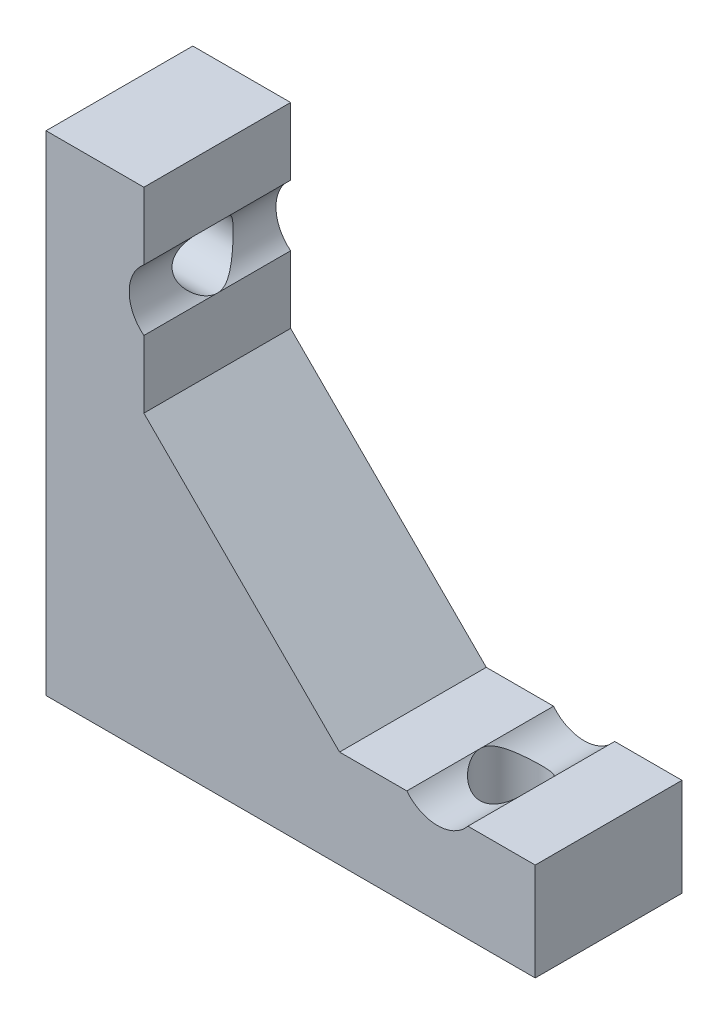
SolidWorks part; units mm, degrees
material "Aleación 1060"
ref_plane "Alzado" through (0, 0, 0) normal (0, 0, 1) x (1, 0, 0)
ref_plane "Planta" through (0, 0, 0) normal (0, 1, 0) x (1, 0, 0)
ref_plane "Vista lateral" through (0, 0, 0) normal (1, 0, 0) x (0, 0, -1)
sketch "Croquis1" plane through (0, 0, 0) normal (0, 0, 1) x (1, 0, 0)
  line L0 (0, 0) -> (0, 20)
  line L1 (0, 0) -> (20, 0)
  line L2 (0, 20) -> (4, 20)
  line L3 (20, 0) -> (20, 4)
  line L4 (4, 20) -> (4, 12)
  line L5 (20, 4) -> (12, 4)
  line L6 (4, 12) -> (12, 4)
  dimension "D1" = 20
  dimension "D2" = 20
  dimension "D3" = 4
  dimension "D4" = 4
  dimension "D5" = 8
  dimension "D6" = 8
extrude "Saliente-Extruir1" add sketch "Croquis1" along normal blind 6
sketch "Croquis3" plane through (0, 4, 0) normal (0, 1, 0) x (1, 0, 0)
  line L0 (20, -6) -> (20, 0) construction
  line L1 (20, 0) -> (12, 0) construction
  circle A0 centre (16, -3) radius 1.25
  point P5 (16, 0)
  point P9 (20, -3)
  dimension "D1" = 2.5
extrude "Cortar-Extruir1" cut sketch "Croquis3" against normal up to vertex (4 mm away)
sketch "Croquis4" plane through (4, 0, 0) normal (1, 0, 0) x (0, 0, -1)
  line L0 (0, 12) -> (0, 20) construction
  line L1 (-6, 20) -> (0, 20) construction
  circle A0 centre (-3, 16) radius 1.25
  point P5 (0, 16)
  point P9 (-3, 20)
  dimension "D1" = 2.5
extrude "Cortar-Extruir2" cut sketch "Croquis4" against normal up to vertex (4 mm away)
sketch "Croquis5" plane through (0, 0, 6) normal (0, 0, 1) x (1, 0, 0)
  line L0 (20, 4) -> (12, 4) construction
  line L1 (0, 0) -> (11.2603, 11.2603) construction
  circle A0 centre (16, 5) radius 1.6
  circle A1 centre (5, 16) radius 1.6
  point P10 (16, 4)
  dimension "D1" = 1
  dimension "D2" = 3.2
extrude "Cortar-Extruir3" cut sketch "Croquis5" against normal up to vertex (6 mm away)
